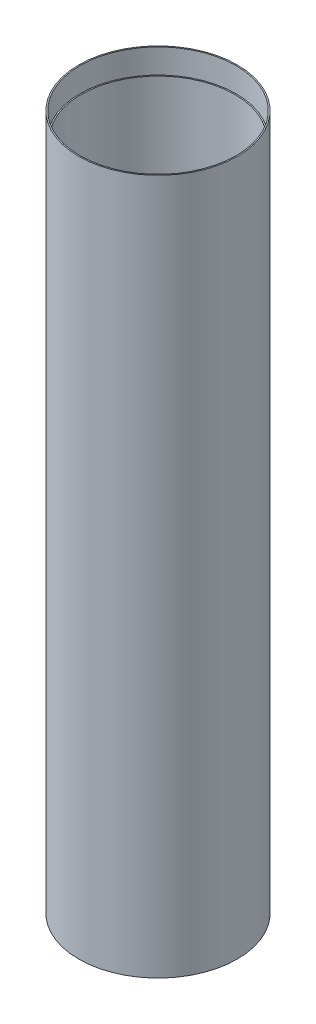
SolidWorks part; units mm, degrees
material "BUTYL"
ref_plane "Płaszczyzna przednia" through (0, 0, 0) normal (0, 0, 1) x (1, 0, 0)
ref_plane "Płaszczyzna górna" through (0, 0, 0) normal (0, 1, 0) x (1, 0, 0)
ref_plane "Płaszczyzna prawa" through (0, 0, 0) normal (1, 0, 0) x (0, 0, -1)
sketch "Szkic1" plane through (0, 0, 0) normal (0, 0, 1) x (1, 0, 0)
  line L0 (64, 285) -> (65, 285)
  line L1 (65, 285) -> (65, -285)
  line L2 (65, -285) -> (64, -285)
  line L3 (64, -285) -> (64, -265)
  line L4 (64, -265) -> (63, -265)
  line L5 (63, -265) -> (63, 265)
  line L6 (63, 265) -> (64, 265)
  line L7 (64, 265) -> (64, 285)
  line L8 (0, 0) -> (0, 92.2309) construction
  point P2 (63, 0)
  dimension "D1" = 530
  dimension "D2" = 570
  dimension "D3" = 20
  dimension "D4" = 2
  dimension "D5" = 63
  dimension "3" = 1
  dimension "D6" = 1
revolve "Obrót1" add sketch "Szkic1" angle 360 about L8
